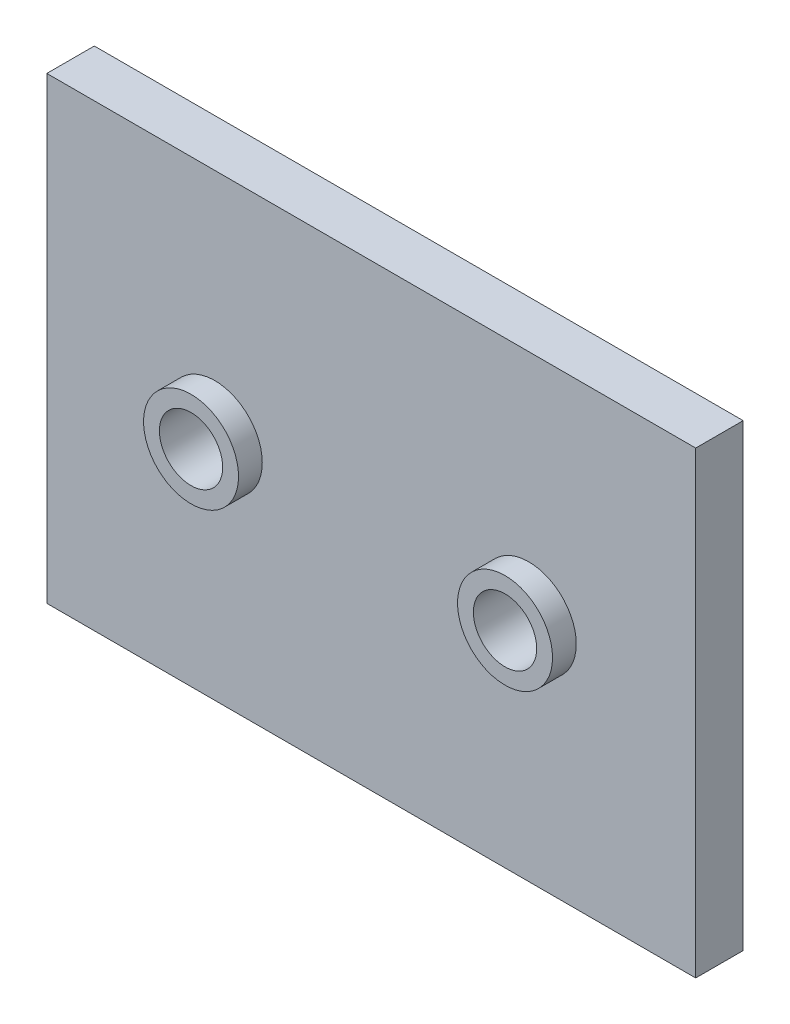
SolidWorks part; units mm, degrees
ref_plane "Front" through (0, 0, 0) normal (0, 0, 1) x (1, 0, 0)
ref_plane "Top" through (0, 0, 0) normal (0, 1, 0) x (1, 0, 0)
ref_plane "Right" through (0, 0, 0) normal (1, 0, 0) x (0, 0, -1)
sketch "Sketch1" plane through (0, 0, 0) normal (0, 0, 1) x (1, 0, 0)
  line L1 (-20.5, 14.5) -> (20.5, 14.5)
  line L2 (-20.5, 14.5) -> (-20.5, -14.5)
  line L3 (-20.5, -14.5) -> (20.5, -14.5)
  line L4 (20.5, 14.5) -> (20.5, -14.5)
  line L5 (-20.5, 14.5) -> (20.5, -14.5) construction
  line L6 (-20.5, -14.5) -> (20.5, 14.5) construction
  point P0 (0, 0)
  dimension "D1" = 41
  dimension "D2" = 29
extrude "Boss-Extrude1" add sketch "Sketch1" along normal blind 3
move or copy body "Body-Move/Copy1" bodies to move or copy 101 copy no translate (0.5, 0.5, 0)
sketch "Sketch11" plane through (0, 0, 3) normal (0, 0, 1) x (1, 0, 0)
  circle A0 centre (-9.3872, 0.5) radius 3
  circle A1 centre (10.4529, 0.5) radius 3
  point P0 (-9.3872, 0.5)
  point P1 (10.4529, 0.5)
  dimension "D1" = 6
  dimension "D2" = 6
extrude "Boss-Extrude2" add sketch "Sketch11" along normal blind 1.5
hole_wizard "Ø4.0 (4) Diameter Hole1" positions "Sketch14" profile "Sketch15" hole size "Ø4.0" standard "ANSI Metric" end condition up to next
sketch "Sketch14" plane through (0, 0, 4.5) normal (0, 0, 1) x (1, 0, 0)
  point P0 (-9.3872, 0.5)
  point P3 (10.4529, 0.5)
sketch "Sketch15" plane through (-9.3872, 0.5, 4.5) normal (1, 0, 0) x (0, -1, 0)
  line L0 (0, 0) -> (0, 4.5)
  line L1 (0, 4.5) -> (2, 4.5)
  line L2 (2, 4.5) -> (2, 0)
  line L5 (2, 0) -> (0, 0)
  line L11 (0, -6.35) -> (0, 107.95) construction
  dimension "Thru Hole Dia." = 4
  dimension "Thru Hole Depth" = 4.5
move or copy body "Body-Move/Copy8" bodies to move or copy 104 copy no translate (27.7957, 0, 0)
